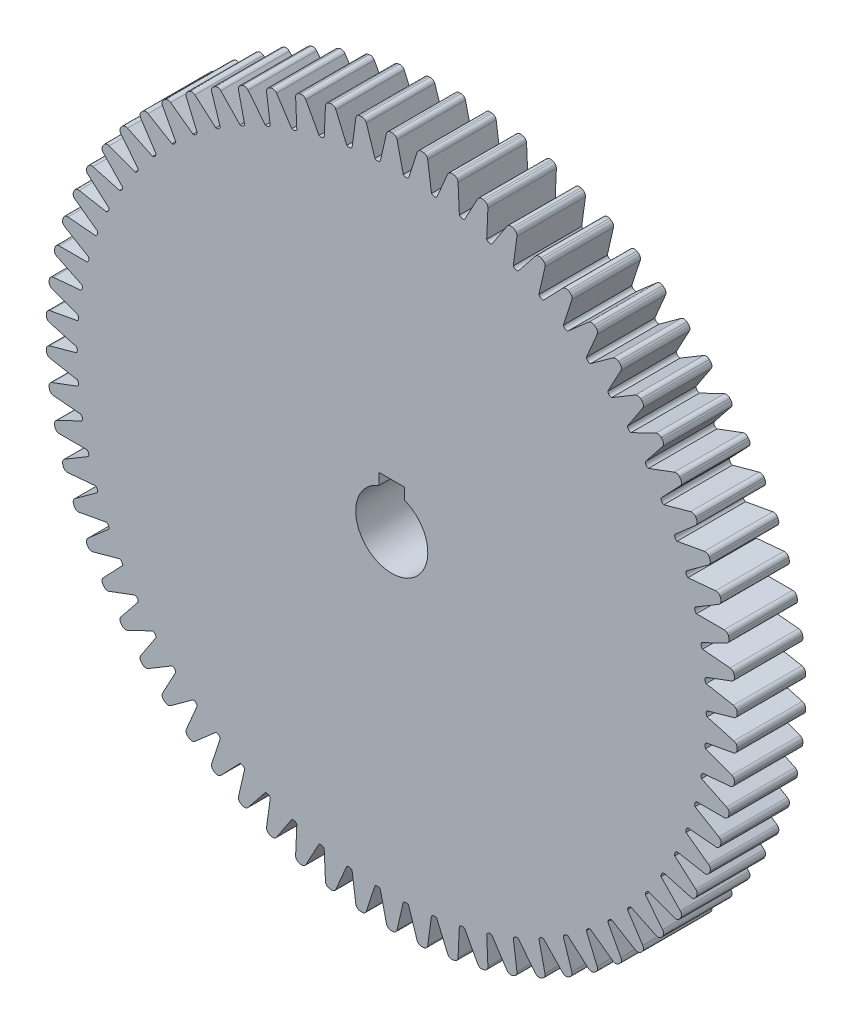
SolidWorks part; units mm, degrees
ref_plane "Front Plane" through (0, 0, 0) normal (0, 0, 1) x (1, 0, 0)
ref_plane "Top Plane" through (0, 0, 0) normal (0, 1, 0) x (1, 0, 0)
ref_plane "Right Plane" through (0, 0, 0) normal (1, 0, 0) x (0, 0, -1)
sketch "Sketch1" plane through (0, 0, 0) normal (0, 0, 1) x (1, 0, 0)
  line L0 (0, 0) -> (0, 6.9703) construction
  line L1 (-0.1016, 38.3651) -> (0.1016, 38.3651)
  line L2 (-0.5889, 37.9767) -> (-1.276, 34.9767)
  line L3 (0.5889, 37.9767) -> (1.276, 34.9767)
  line L4 (3.3379, 38.2198) -> (3.5402, 38.2016)
  line L5 (3.9908, 37.7711) -> (4.4061, 34.7216)
  line L6 (2.8176, 37.8766) -> (1.8645, 34.9503)
  line L7 (6.7504, 37.7667) -> (6.9503, 37.7304)
  line L8 (7.3605, 37.2613) -> (7.5008, 34.1868)
  line L9 (6.2015, 37.4716) -> (4.9899, 34.6425)
  line L10 (10.1086, 37.0096) -> (10.3044, 36.9555)
  line L11 (10.6709, 36.4515) -> (10.5351, 33.3768)
  line L12 (9.5355, 36.7648) -> (8.0751, 34.0557)
  line L13 (13.3855, 35.9544) -> (13.5756, 35.8831)
  line L14 (13.8955, 35.3482) -> (13.4845, 32.2981)
  line L15 (12.7927, 35.7621) -> (11.0953, 33.1948)
  line L16 (16.5545, 34.6098) -> (16.7375, 34.5217)
  line L17 (17.0081, 33.9603) -> (16.3254, 30.9593)
  line L18 (15.9469, 34.4714) -> (14.0262, 32.0666)
  line L19 (19.5903, 32.9866) -> (19.7646, 32.8824)
  line L20 (19.9838, 32.299) -> (19.0349, 29.3713)
  line L21 (18.9727, 32.9031) -> (16.8442, 30.6802)
  line L22 (22.4683, 31.0977) -> (22.6326, 30.9783)
  line L23 (22.7986, 30.3777) -> (21.5911, 27.5468)
  line L24 (21.8457, 31.07) -> (19.5265, 29.0468)
  line L25 (25.1654, 28.9585) -> (25.3184, 28.8249)
  line L26 (25.4299, 28.2117) -> (23.9734, 25.5005)
  line L27 (24.5428, 28.9867) -> (22.0517, 27.1795)
  line L28 (27.6599, 26.5861) -> (27.8003, 26.4393)
  line L29 (27.8564, 25.8186) -> (26.1628, 23.2489)
  line L30 (27.0424, 26.67) -> (24.3992, 25.0934)
  line L31 (29.9317, 23.9997) -> (30.0584, 23.8409)
  line L32 (30.0586, 23.2177) -> (28.1415, 20.81)
  line L33 (29.3242, 24.1386) -> (26.5504, 22.8052)
  line L34 (31.9626, 21.22) -> (32.0745, 21.0505)
  line L35 (32.0188, 20.4298) -> (29.8936, 18.2037)
  line L36 (31.3699, 21.4128) -> (28.4877, 20.3335)
  line L37 (33.736, 18.2695) -> (33.8323, 18.0906)
  line L38 (33.7212, 17.4774) -> (31.405, 15.4508)
  line L39 (33.1631, 18.5146) -> (30.1957, 17.698)
  line L40 (35.2379, 15.1718) -> (35.3177, 14.9851)
  line L41 (35.1521, 14.3843) -> (32.6636, 12.5734)
  line L42 (34.6892, 15.4674) -> (31.6606, 14.92)
  line L43 (36.456, 11.9521) -> (36.5188, 11.7589)
  line L44 (36.3, 11.1753) -> (33.6591, 9.5949)
  line L45 (35.936, 12.2956) -> (32.8706, 12.0219)
  line L46 (37.3806, 8.6361) -> (37.4258, 8.438)
  line L47 (37.1556, 7.8764) -> (34.3837, 6.5391)
  line L48 (36.8935, 9.0248) -> (33.8159, 9.027)
  line L49 (38.0043, 5.2505) -> (38.0315, 5.0492)
  line L50 (37.7121, 4.5141) -> (34.8315, 3.4306)
  line L51 (37.554, 5.6814) -> (34.4889, 5.9595)
  line L52 (38.3219, 1.8227) -> (38.331, 1.6198)
  line L53 (37.9649, 1.1155) -> (34.9988, 0.2945)
  line L54 (37.9121, 2.2922) -> (34.8843, 2.8439)
  line L55 (38.331, -1.6198) -> (38.3219, -1.8227)
  line L56 (37.9121, -2.2922) -> (34.8843, -2.8439)
  line L57 (37.9649, -1.1155) -> (34.9988, -0.2945)
  line L58 (38.0315, -5.0492) -> (38.0043, -5.2505)
  line L59 (37.554, -5.6814) -> (34.4889, -5.9595)
  line L60 (37.7121, -4.5141) -> (34.8315, -3.4306)
  line L61 (37.4258, -8.438) -> (37.3806, -8.6361)
  line L62 (36.8935, -9.0248) -> (33.8159, -9.027)
  line L63 (37.1556, -7.8764) -> (34.3837, -6.5391)
  line L64 (36.5188, -11.7589) -> (36.456, -11.9521)
  line L65 (35.936, -12.2956) -> (32.8706, -12.0219)
  line L66 (36.3, -11.1753) -> (33.6591, -9.5949)
  line L67 (35.3177, -14.9851) -> (35.2379, -15.1718)
  line L68 (34.6892, -15.4674) -> (31.6606, -14.92)
  line L69 (35.1521, -14.3843) -> (32.6636, -12.5734)
  line L70 (33.8323, -18.0906) -> (33.736, -18.2695)
  line L71 (33.1631, -18.5146) -> (30.1957, -17.698)
  line L72 (33.7212, -17.4774) -> (31.405, -15.4508)
  line L73 (32.0745, -21.0505) -> (31.9626, -21.22)
  line L74 (31.3699, -21.4128) -> (28.4877, -20.3335)
  line L75 (32.0188, -20.4298) -> (29.8936, -18.2037)
  line L76 (30.0584, -23.8409) -> (29.9317, -23.9997)
  line L77 (29.3242, -24.1386) -> (26.5504, -22.8052)
  line L78 (30.0586, -23.2177) -> (28.1415, -20.81)
  line L79 (27.8003, -26.4393) -> (27.6599, -26.5861)
  line L80 (27.0424, -26.67) -> (24.3992, -25.0934)
  line L81 (27.8564, -25.8186) -> (26.1628, -23.2489)
  line L82 (25.3184, -28.8249) -> (25.1654, -28.9585)
  line L83 (24.5428, -28.9867) -> (22.0517, -27.1795)
  line L84 (25.4299, -28.2117) -> (23.9734, -25.5005)
  line L85 (22.6326, -30.9783) -> (22.4683, -31.0977)
  line L86 (21.8457, -31.07) -> (19.5265, -29.0468)
  line L87 (22.7986, -30.3777) -> (21.5911, -27.5468)
  line L88 (19.7646, -32.8824) -> (19.5903, -32.9866)
  line L89 (18.9727, -32.9031) -> (16.8442, -30.6802)
  line L90 (19.9838, -32.299) -> (19.0349, -29.3713)
  line L91 (16.7375, -34.5217) -> (16.5545, -34.6098)
  line L92 (15.9469, -34.4714) -> (14.0262, -32.0666)
  line L93 (17.0081, -33.9603) -> (16.3254, -30.9593)
  line L94 (13.5756, -35.8831) -> (13.3855, -35.9544)
  line L95 (12.7927, -35.7621) -> (11.0953, -33.1948)
  line L96 (13.8955, -35.3482) -> (13.4845, -32.2981)
  line L97 (10.3044, -36.9555) -> (10.1086, -37.0096)
  line L98 (9.5355, -36.7648) -> (8.0751, -34.0557)
  line L99 (10.6709, -36.4515) -> (10.5351, -33.3768)
  line L100 (6.9503, -37.7304) -> (6.7504, -37.7667)
  line L101 (6.2015, -37.4716) -> (4.9899, -34.6425)
  line L102 (7.3605, -37.2613) -> (7.5008, -34.1868)
  line L103 (3.5402, -38.2016) -> (3.3379, -38.2198)
  line L104 (2.8176, -37.8766) -> (1.8645, -34.9503)
  line L105 (3.9908, -37.7711) -> (4.4061, -34.7216)
  line L106 (0.1016, -38.3651) -> (-0.1016, -38.3651)
  line L107 (-0.5889, -37.9767) -> (-1.276, -34.9767)
  line L108 (0.5889, -37.9767) -> (1.276, -34.9767)
  line L109 (-3.3379, -38.2198) -> (-3.5402, -38.2016)
  line L110 (-3.9908, -37.7711) -> (-4.4061, -34.7216)
  line L111 (-2.8176, -37.8766) -> (-1.8645, -34.9503)
  line L112 (-6.7504, -37.7667) -> (-6.9503, -37.7304)
  line L113 (-7.3605, -37.2613) -> (-7.5008, -34.1868)
  line L114 (-6.2015, -37.4716) -> (-4.9899, -34.6425)
  line L115 (-10.1086, -37.0096) -> (-10.3044, -36.9555)
  line L116 (-10.6709, -36.4515) -> (-10.5351, -33.3768)
  line L117 (-9.5355, -36.7648) -> (-8.0751, -34.0557)
  line L118 (-13.3855, -35.9544) -> (-13.5756, -35.8831)
  line L119 (-13.8955, -35.3482) -> (-13.4845, -32.2981)
  line L120 (-12.7927, -35.7621) -> (-11.0953, -33.1948)
  line L121 (-16.5545, -34.6098) -> (-16.7375, -34.5217)
  line L122 (-17.0081, -33.9603) -> (-16.3254, -30.9593)
  line L123 (-15.9469, -34.4714) -> (-14.0262, -32.0666)
  line L124 (-19.5903, -32.9866) -> (-19.7646, -32.8824)
  line L125 (-19.9838, -32.299) -> (-19.0349, -29.3713)
  line L126 (-18.9727, -32.9031) -> (-16.8442, -30.6802)
  line L127 (-22.4683, -31.0977) -> (-22.6326, -30.9783)
  line L128 (-22.7986, -30.3777) -> (-21.5911, -27.5468)
  line L129 (-21.8457, -31.07) -> (-19.5265, -29.0468)
  line L130 (-25.1654, -28.9585) -> (-25.3184, -28.8249)
  line L131 (-25.4299, -28.2117) -> (-23.9734, -25.5005)
  line L132 (-24.5428, -28.9867) -> (-22.0517, -27.1795)
  line L133 (-27.6599, -26.5861) -> (-27.8003, -26.4393)
  line L134 (-27.8564, -25.8186) -> (-26.1628, -23.2489)
  line L135 (-27.0424, -26.67) -> (-24.3992, -25.0934)
  line L136 (-29.9317, -23.9997) -> (-30.0584, -23.8409)
  line L137 (-30.0586, -23.2177) -> (-28.1415, -20.81)
  line L138 (-29.3242, -24.1386) -> (-26.5504, -22.8052)
  line L139 (-31.9626, -21.22) -> (-32.0745, -21.0505)
  line L140 (-32.0188, -20.4298) -> (-29.8936, -18.2037)
  line L141 (-31.3699, -21.4128) -> (-28.4877, -20.3335)
  line L142 (-33.736, -18.2695) -> (-33.8323, -18.0906)
  line L143 (-33.7212, -17.4774) -> (-31.405, -15.4508)
  line L144 (-33.1631, -18.5146) -> (-30.1957, -17.698)
  line L145 (-35.2379, -15.1718) -> (-35.3177, -14.9851)
  line L146 (-35.1521, -14.3843) -> (-32.6636, -12.5734)
  line L147 (-34.6892, -15.4674) -> (-31.6606, -14.92)
  line L148 (-36.456, -11.9521) -> (-36.5188, -11.7589)
  line L149 (-36.3, -11.1753) -> (-33.6591, -9.5949)
  line L150 (-35.936, -12.2956) -> (-32.8706, -12.0219)
  line L151 (-37.3806, -8.6361) -> (-37.4258, -8.438)
  line L152 (-37.1556, -7.8764) -> (-34.3837, -6.5391)
  line L153 (-36.8935, -9.0248) -> (-33.8159, -9.027)
  line L154 (-38.0043, -5.2505) -> (-38.0315, -5.0492)
  line L155 (-37.7121, -4.5141) -> (-34.8315, -3.4306)
  line L156 (-37.554, -5.6814) -> (-34.4889, -5.9595)
  line L157 (-38.3219, -1.8227) -> (-38.331, -1.6198)
  line L158 (-37.9649, -1.1155) -> (-34.9988, -0.2945)
  line L159 (-37.9121, -2.2922) -> (-34.8843, -2.8439)
  line L160 (-38.331, 1.6198) -> (-38.3219, 1.8227)
  line L161 (-37.9121, 2.2922) -> (-34.8843, 2.8439)
  line L162 (-37.9649, 1.1155) -> (-34.9988, 0.2945)
  line L163 (-38.0315, 5.0492) -> (-38.0043, 5.2505)
  line L164 (-37.554, 5.6814) -> (-34.4889, 5.9595)
  line L165 (-37.7121, 4.5141) -> (-34.8315, 3.4306)
  line L166 (-37.4258, 8.438) -> (-37.3806, 8.6361)
  line L167 (-36.8935, 9.0248) -> (-33.8159, 9.027)
  line L168 (-37.1556, 7.8764) -> (-34.3837, 6.5391)
  line L169 (-36.5188, 11.7589) -> (-36.456, 11.9521)
  line L170 (-35.936, 12.2956) -> (-32.8706, 12.0219)
  line L171 (-36.3, 11.1753) -> (-33.6591, 9.5949)
  line L172 (-35.3177, 14.9851) -> (-35.2379, 15.1718)
  line L173 (-34.6892, 15.4674) -> (-31.6606, 14.92)
  line L174 (-35.1521, 14.3843) -> (-32.6636, 12.5734)
  line L175 (-33.8323, 18.0906) -> (-33.736, 18.2695)
  line L176 (-33.1631, 18.5146) -> (-30.1957, 17.698)
  line L177 (-33.7212, 17.4774) -> (-31.405, 15.4508)
  line L178 (-32.0745, 21.0505) -> (-31.9626, 21.22)
  line L179 (-31.3699, 21.4128) -> (-28.4877, 20.3335)
  line L180 (-32.0188, 20.4298) -> (-29.8936, 18.2037)
  line L181 (-30.0584, 23.8409) -> (-29.9317, 23.9997)
  line L182 (-29.3242, 24.1386) -> (-26.5504, 22.8052)
  line L183 (-30.0586, 23.2177) -> (-28.1415, 20.81)
  line L184 (-27.8003, 26.4393) -> (-27.6599, 26.5861)
  line L185 (-27.0424, 26.67) -> (-24.3992, 25.0934)
  line L186 (-27.8564, 25.8186) -> (-26.1628, 23.2489)
  line L187 (-25.3184, 28.8249) -> (-25.1654, 28.9585)
  line L188 (-24.5428, 28.9867) -> (-22.0517, 27.1795)
  line L189 (-25.4299, 28.2117) -> (-23.9734, 25.5005)
  line L190 (-22.6326, 30.9783) -> (-22.4683, 31.0977)
  line L191 (-21.8457, 31.07) -> (-19.5265, 29.0468)
  line L192 (-22.7986, 30.3777) -> (-21.5911, 27.5468)
  line L193 (-19.7646, 32.8824) -> (-19.5903, 32.9866)
  line L194 (-18.9727, 32.9031) -> (-16.8442, 30.6802)
  line L195 (-19.9838, 32.299) -> (-19.0349, 29.3713)
  line L196 (-16.7375, 34.5217) -> (-16.5545, 34.6098)
  line L197 (-15.9469, 34.4714) -> (-14.0262, 32.0666)
  line L198 (-17.0081, 33.9603) -> (-16.3254, 30.9593)
  line L199 (-13.5756, 35.8831) -> (-13.3855, 35.9544)
  line L200 (-12.7927, 35.7621) -> (-11.0953, 33.1948)
  line L201 (-13.8955, 35.3482) -> (-13.4845, 32.2981)
  line L202 (-10.3044, 36.9555) -> (-10.1086, 37.0096)
  line L203 (-9.5355, 36.7648) -> (-8.0751, 34.0557)
  line L204 (-10.6709, 36.4515) -> (-10.5351, 33.3768)
  line L205 (-6.9503, 37.7304) -> (-6.7504, 37.7667)
  line L206 (-6.2015, 37.4716) -> (-4.9899, 34.6425)
  line L207 (-7.3605, 37.2613) -> (-7.5008, 34.1868)
  line L208 (-3.5402, 38.2016) -> (-3.3379, 38.2198)
  line L209 (-2.8176, 37.8766) -> (-1.8645, 34.9503)
  line L210 (-3.9908, 37.7711) -> (-4.4061, 34.7216)
  arc A1 (0.1016, 38.3651) -> (0.5889, 37.9767) centre (0.1016, 37.8651) cw
  arc A2 (-0.1016, 38.3651) -> (-0.5889, 37.9767) centre (-0.1016, 37.8651) ccw
  arc A281 (3.3379, 38.2198) -> (2.8176, 37.8766) centre (3.2931, 37.7218) ccw
  arc A282 (3.5402, 38.2016) -> (3.9908, 37.7711) centre (3.4954, 37.7036) cw
  arc A283 (6.7504, 37.7667) -> (6.2015, 37.4716) centre (6.6612, 37.2747) ccw
  arc A284 (6.9503, 37.7304) -> (7.3605, 37.2613) centre (6.861, 37.2385) cw
  arc A285 (10.1086, 37.0096) -> (9.5355, 36.7648) centre (9.9756, 36.5276) ccw
  arc A286 (10.3044, 36.9555) -> (10.6709, 36.4515) centre (10.1714, 36.4736) cw
  arc A287 (13.3855, 35.9544) -> (12.7927, 35.7621) centre (13.2098, 35.4863) ccw
  arc A288 (13.5756, 35.8831) -> (13.8955, 35.3482) centre (13.3999, 35.415) cw
  arc A289 (16.5545, 34.6098) -> (15.9469, 34.4714) centre (16.3376, 34.1594) ccw
  arc A290 (16.7375, 34.5217) -> (17.0081, 33.9603) centre (16.5206, 34.0712) cw
  arc A291 (19.5903, 32.9866) -> (18.9727, 32.9031) centre (19.3338, 32.5574) ccw
  arc A292 (19.7646, 32.8824) -> (19.9838, 32.299) centre (19.5082, 32.4532) cw
  arc A293 (22.4683, 31.0977) -> (21.8457, 31.07) centre (22.1744, 30.6932) ccw
  arc A294 (22.6326, 30.9783) -> (22.7986, 30.3777) centre (22.3387, 30.5738) cw
  arc A295 (25.1654, 28.9585) -> (24.5428, 28.9867) centre (24.8364, 28.582) ccw
  arc A296 (25.3184, 28.8249) -> (25.4299, 28.2117) centre (24.9894, 28.4483) cw
  arc A297 (27.6599, 26.5861) -> (27.0424, 26.67) centre (27.2985, 26.2406) ccw
  arc A298 (27.8003, 26.4393) -> (27.8564, 25.8186) centre (27.4389, 26.0938) cw
  arc A299 (29.9317, 23.9997) -> (29.3242, 24.1386) centre (29.5408, 23.6879) ccw
  arc A300 (30.0584, 23.8409) -> (30.0586, 23.2177) centre (29.6675, 23.5291) cw
  arc A301 (31.9626, 21.22) -> (31.3699, 21.4128) centre (31.5453, 20.9445) ccw
  arc A302 (32.0745, 21.0505) -> (32.0188, 20.4298) centre (31.6572, 20.775) cw
  arc A303 (33.736, 18.2695) -> (33.1631, 18.5146) centre (33.2957, 18.0325) ccw
  arc A304 (33.8323, 18.0906) -> (33.7212, 17.4774) centre (33.392, 17.8537) cw
  arc A305 (35.2379, 15.1718) -> (34.6892, 15.4674) centre (34.7781, 14.9753) ccw
  arc A306 (35.3177, 14.9851) -> (35.1521, 14.3843) centre (34.8579, 14.7886) cw
  arc A307 (36.456, 11.9521) -> (35.936, 12.2956) centre (35.9805, 11.7976) ccw
  arc A308 (36.5188, 11.7589) -> (36.3, 11.1753) centre (36.0433, 11.6044) cw
  arc A309 (37.3806, 8.6361) -> (36.8935, 9.0248) centre (36.8932, 8.5248) ccw
  arc A310 (37.4258, 8.438) -> (37.1556, 7.8764) centre (36.9384, 8.3268) cw
  arc A311 (38.0043, 5.2505) -> (37.554, 5.6814) centre (37.5088, 5.1834) ccw
  arc A312 (38.0315, 5.0492) -> (37.7121, 4.5141) centre (37.5361, 4.9821) cw
  arc A313 (38.3219, 1.8227) -> (37.9121, 2.2922) centre (37.8224, 1.8003) ccw
  arc A314 (38.331, 1.6198) -> (37.9649, 1.1155) centre (37.8315, 1.5974) cw
  arc A315 (38.331, -1.6198) -> (37.9649, -1.1155) centre (37.8315, -1.5974) ccw
  arc A316 (38.3219, -1.8227) -> (37.9121, -2.2922) centre (37.8224, -1.8003) cw
  arc A317 (38.0315, -5.0492) -> (37.7121, -4.5141) centre (37.5361, -4.9821) ccw
  arc A318 (38.0043, -5.2505) -> (37.554, -5.6814) centre (37.5088, -5.1834) cw
  arc A319 (37.4258, -8.438) -> (37.1556, -7.8764) centre (36.9384, -8.3268) ccw
  arc A320 (37.3806, -8.6361) -> (36.8935, -9.0248) centre (36.8932, -8.5248) cw
  arc A321 (36.5188, -11.7589) -> (36.3, -11.1753) centre (36.0433, -11.6044) ccw
  arc A322 (36.456, -11.9521) -> (35.936, -12.2956) centre (35.9805, -11.7976) cw
  arc A323 (35.3177, -14.9851) -> (35.1521, -14.3843) centre (34.8579, -14.7886) ccw
  arc A324 (35.2379, -15.1718) -> (34.6892, -15.4674) centre (34.7781, -14.9753) cw
  arc A325 (33.8323, -18.0906) -> (33.7212, -17.4774) centre (33.392, -17.8537) ccw
  arc A326 (33.736, -18.2695) -> (33.1631, -18.5146) centre (33.2957, -18.0325) cw
  arc A327 (32.0745, -21.0505) -> (32.0188, -20.4298) centre (31.6572, -20.775) ccw
  arc A328 (31.9626, -21.22) -> (31.3699, -21.4128) centre (31.5453, -20.9445) cw
  arc A329 (30.0584, -23.8409) -> (30.0586, -23.2177) centre (29.6675, -23.5291) ccw
  arc A330 (29.9317, -23.9997) -> (29.3242, -24.1386) centre (29.5408, -23.6879) cw
  arc A331 (27.8003, -26.4393) -> (27.8564, -25.8186) centre (27.4389, -26.0938) ccw
  arc A332 (27.6599, -26.5861) -> (27.0424, -26.67) centre (27.2985, -26.2406) cw
  arc A333 (25.3184, -28.8249) -> (25.4299, -28.2117) centre (24.9894, -28.4483) ccw
  arc A334 (25.1654, -28.9585) -> (24.5428, -28.9867) centre (24.8364, -28.582) cw
  arc A335 (22.6326, -30.9783) -> (22.7986, -30.3777) centre (22.3387, -30.5738) ccw
  arc A336 (22.4683, -31.0977) -> (21.8457, -31.07) centre (22.1744, -30.6932) cw
  arc A337 (19.7646, -32.8824) -> (19.9838, -32.299) centre (19.5082, -32.4532) ccw
  arc A338 (19.5903, -32.9866) -> (18.9727, -32.9031) centre (19.3338, -32.5574) cw
  arc A339 (16.7375, -34.5217) -> (17.0081, -33.9603) centre (16.5206, -34.0712) ccw
  arc A340 (16.5545, -34.6098) -> (15.9469, -34.4714) centre (16.3376, -34.1594) cw
  arc A341 (13.5756, -35.8831) -> (13.8955, -35.3482) centre (13.3999, -35.415) ccw
  arc A342 (13.3855, -35.9544) -> (12.7927, -35.7621) centre (13.2098, -35.4863) cw
  arc A343 (10.3044, -36.9555) -> (10.6709, -36.4515) centre (10.1714, -36.4736) ccw
  arc A344 (10.1086, -37.0096) -> (9.5355, -36.7648) centre (9.9756, -36.5276) cw
  arc A345 (6.9503, -37.7304) -> (7.3605, -37.2613) centre (6.861, -37.2385) ccw
  arc A346 (6.7504, -37.7667) -> (6.2015, -37.4716) centre (6.6612, -37.2747) cw
  arc A347 (3.5402, -38.2016) -> (3.9908, -37.7711) centre (3.4954, -37.7036) ccw
  arc A348 (3.3379, -38.2198) -> (2.8176, -37.8766) centre (3.2931, -37.7218) cw
  arc A349 (0.1016, -38.3651) -> (0.5889, -37.9767) centre (0.1016, -37.8651) ccw
  arc A350 (-0.1016, -38.3651) -> (-0.5889, -37.9767) centre (-0.1016, -37.8651) cw
  arc A351 (-3.3379, -38.2198) -> (-2.8176, -37.8766) centre (-3.2931, -37.7218) ccw
  arc A352 (-3.5402, -38.2016) -> (-3.9908, -37.7711) centre (-3.4954, -37.7036) cw
  arc A353 (-6.7504, -37.7667) -> (-6.2015, -37.4716) centre (-6.6612, -37.2747) ccw
  arc A354 (-6.9503, -37.7304) -> (-7.3605, -37.2613) centre (-6.861, -37.2385) cw
  arc A355 (-10.1086, -37.0096) -> (-9.5355, -36.7648) centre (-9.9756, -36.5276) ccw
  arc A356 (-10.3044, -36.9555) -> (-10.6709, -36.4515) centre (-10.1714, -36.4736) cw
  arc A357 (-13.3855, -35.9544) -> (-12.7927, -35.7621) centre (-13.2098, -35.4863) ccw
  arc A358 (-13.5756, -35.8831) -> (-13.8955, -35.3482) centre (-13.3999, -35.415) cw
  arc A359 (-16.5545, -34.6098) -> (-15.9469, -34.4714) centre (-16.3376, -34.1594) ccw
  arc A360 (-16.7375, -34.5217) -> (-17.0081, -33.9603) centre (-16.5206, -34.0712) cw
  arc A361 (-19.5903, -32.9866) -> (-18.9727, -32.9031) centre (-19.3338, -32.5574) ccw
  arc A362 (-19.7646, -32.8824) -> (-19.9838, -32.299) centre (-19.5082, -32.4532) cw
  arc A363 (-22.4683, -31.0977) -> (-21.8457, -31.07) centre (-22.1744, -30.6932) ccw
  arc A364 (-22.6326, -30.9783) -> (-22.7986, -30.3777) centre (-22.3387, -30.5738) cw
  arc A365 (-25.1654, -28.9585) -> (-24.5428, -28.9867) centre (-24.8364, -28.582) ccw
  arc A366 (-25.3184, -28.8249) -> (-25.4299, -28.2117) centre (-24.9894, -28.4483) cw
  arc A367 (-27.6599, -26.5861) -> (-27.0424, -26.67) centre (-27.2985, -26.2406) ccw
  arc A368 (-27.8003, -26.4393) -> (-27.8564, -25.8186) centre (-27.4389, -26.0938) cw
  arc A369 (-29.9317, -23.9997) -> (-29.3242, -24.1386) centre (-29.5408, -23.6879) ccw
  arc A370 (-30.0584, -23.8409) -> (-30.0586, -23.2177) centre (-29.6675, -23.5291) cw
  arc A371 (-31.9626, -21.22) -> (-31.3699, -21.4128) centre (-31.5453, -20.9445) ccw
  arc A372 (-32.0745, -21.0505) -> (-32.0188, -20.4298) centre (-31.6572, -20.775) cw
  arc A373 (-33.736, -18.2695) -> (-33.1631, -18.5146) centre (-33.2957, -18.0325) ccw
  arc A374 (-33.8323, -18.0906) -> (-33.7212, -17.4774) centre (-33.392, -17.8537) cw
  arc A375 (-35.2379, -15.1718) -> (-34.6892, -15.4674) centre (-34.7781, -14.9753) ccw
  arc A376 (-35.3177, -14.9851) -> (-35.1521, -14.3843) centre (-34.8579, -14.7886) cw
  arc A377 (-36.456, -11.9521) -> (-35.936, -12.2956) centre (-35.9805, -11.7976) ccw
  arc A378 (-36.5188, -11.7589) -> (-36.3, -11.1753) centre (-36.0433, -11.6044) cw
  arc A379 (-37.3806, -8.6361) -> (-36.8935, -9.0248) centre (-36.8932, -8.5248) ccw
  arc A380 (-37.4258, -8.438) -> (-37.1556, -7.8764) centre (-36.9384, -8.3268) cw
  arc A381 (-38.0043, -5.2505) -> (-37.554, -5.6814) centre (-37.5088, -5.1834) ccw
  arc A382 (-38.0315, -5.0492) -> (-37.7121, -4.5141) centre (-37.5361, -4.9821) cw
  arc A383 (-38.3219, -1.8227) -> (-37.9121, -2.2922) centre (-37.8224, -1.8003) ccw
  arc A384 (-38.331, -1.6198) -> (-37.9649, -1.1155) centre (-37.8315, -1.5974) cw
  arc A385 (-38.331, 1.6198) -> (-37.9649, 1.1155) centre (-37.8315, 1.5974) ccw
  arc A386 (-38.3219, 1.8227) -> (-37.9121, 2.2922) centre (-37.8224, 1.8003) cw
  arc A387 (-38.0315, 5.0492) -> (-37.7121, 4.5141) centre (-37.5361, 4.9821) ccw
  arc A388 (-38.0043, 5.2505) -> (-37.554, 5.6814) centre (-37.5088, 5.1834) cw
  arc A389 (-37.4258, 8.438) -> (-37.1556, 7.8764) centre (-36.9384, 8.3268) ccw
  arc A390 (-37.3806, 8.6361) -> (-36.8935, 9.0248) centre (-36.8932, 8.5248) cw
  arc A391 (-36.5188, 11.7589) -> (-36.3, 11.1753) centre (-36.0433, 11.6044) ccw
  arc A392 (-36.456, 11.9521) -> (-35.936, 12.2956) centre (-35.9805, 11.7976) cw
  arc A393 (-35.3177, 14.9851) -> (-35.1521, 14.3843) centre (-34.8579, 14.7886) ccw
  arc A394 (-35.2379, 15.1718) -> (-34.6892, 15.4674) centre (-34.7781, 14.9753) cw
  arc A395 (-33.8323, 18.0906) -> (-33.7212, 17.4774) centre (-33.392, 17.8537) ccw
  arc A396 (-33.736, 18.2695) -> (-33.1631, 18.5146) centre (-33.2957, 18.0325) cw
  arc A397 (-32.0745, 21.0505) -> (-32.0188, 20.4298) centre (-31.6572, 20.775) ccw
  arc A398 (-31.9626, 21.22) -> (-31.3699, 21.4128) centre (-31.5453, 20.9445) cw
  arc A399 (-30.0584, 23.8409) -> (-30.0586, 23.2177) centre (-29.6675, 23.5291) ccw
  arc A400 (-29.9317, 23.9997) -> (-29.3242, 24.1386) centre (-29.5408, 23.6879) cw
  arc A401 (-27.8003, 26.4393) -> (-27.8564, 25.8186) centre (-27.4389, 26.0938) ccw
  arc A402 (-27.6599, 26.5861) -> (-27.0424, 26.67) centre (-27.2985, 26.2406) cw
  arc A403 (-25.3184, 28.8249) -> (-25.4299, 28.2117) centre (-24.9894, 28.4483) ccw
  arc A404 (-25.1654, 28.9585) -> (-24.5428, 28.9867) centre (-24.8364, 28.582) cw
  arc A405 (-22.6326, 30.9783) -> (-22.7986, 30.3777) centre (-22.3387, 30.5738) ccw
  arc A406 (-22.4683, 31.0977) -> (-21.8457, 31.07) centre (-22.1744, 30.6932) cw
  arc A407 (-19.7646, 32.8824) -> (-19.9838, 32.299) centre (-19.5082, 32.4532) ccw
  arc A408 (-19.5903, 32.9866) -> (-18.9727, 32.9031) centre (-19.3338, 32.5574) cw
  arc A409 (-16.7375, 34.5217) -> (-17.0081, 33.9603) centre (-16.5206, 34.0712) ccw
  arc A410 (-16.5545, 34.6098) -> (-15.9469, 34.4714) centre (-16.3376, 34.1594) cw
  arc A411 (-13.5756, 35.8831) -> (-13.8955, 35.3482) centre (-13.3999, 35.415) ccw
  arc A412 (-13.3855, 35.9544) -> (-12.7927, 35.7621) centre (-13.2098, 35.4863) cw
  arc A413 (-10.3044, 36.9555) -> (-10.6709, 36.4515) centre (-10.1714, 36.4736) ccw
  arc A414 (-10.1086, 37.0096) -> (-9.5355, 36.7648) centre (-9.9756, 36.5276) cw
  arc A415 (-6.9503, 37.7304) -> (-7.3605, 37.2613) centre (-6.861, 37.2385) ccw
  arc A416 (-6.7504, 37.7667) -> (-6.2015, 37.4716) centre (-6.6612, 37.2747) cw
  arc A417 (-3.5402, 38.2016) -> (-3.9908, 37.7711) centre (-3.4954, 37.7036) ccw
  arc A418 (-3.3379, 38.2198) -> (-2.8176, 37.8766) centre (-3.2931, 37.7218) cw
  spline S0 degree 2 poles (1.276, 34.9767) (1.5601, 34.7601) (1.8645, 34.9503) knots 0 0 0 1 1 1
  spline S1 degree 2 poles (4.4061, 34.7216) (4.6697, 34.4803) (4.9899, 34.6425) knots 0 0 0 1 1 1
  spline S2 degree 2 poles (7.5008, 34.1868) (7.7417, 33.9229) (8.0751, 34.0557) knots 0 0 0 1 1 1
  spline S3 degree 2 poles (10.5351, 33.3768) (10.7514, 33.0924) (11.0953, 33.1948) knots 0 0 0 1 1 1
  spline S4 degree 2 poles (13.4845, 32.2981) (13.6745, 31.9955) (14.0262, 32.0666) knots 0 0 0 1 1 1
  spline S5 degree 2 poles (16.3254, 30.9593) (16.4875, 30.6409) (16.8442, 30.6802) knots 0 0 0 1 1 1
  spline S6 degree 2 poles (19.0349, 29.3713) (19.1677, 29.0396) (19.5265, 29.0468) knots 0 0 0 1 1 1
  spline S7 degree 2 poles (21.5911, 27.5468) (21.6937, 27.2045) (22.0517, 27.1795) knots 0 0 0 1 1 1
  spline S8 degree 2 poles (23.9734, 25.5005) (24.0449, 25.1504) (24.3992, 25.0934) knots 0 0 0 1 1 1
  spline S9 degree 2 poles (26.1628, 23.2489) (26.2026, 22.8938) (26.5504, 22.8052) knots 0 0 0 1 1 1
  spline S10 degree 2 poles (28.1415, 20.81) (28.1493, 20.4528) (28.4877, 20.3335) knots 0 0 0 1 1 1
  spline S11 degree 2 poles (29.8936, 18.2037) (29.8693, 17.8472) (30.1957, 17.698) knots 0 0 0 1 1 1
  spline S12 degree 2 poles (31.405, 15.4508) (31.3489, 15.0979) (31.6606, 14.92) knots 0 0 0 1 1 1
  spline S13 degree 2 poles (32.6636, 12.5734) (32.5761, 12.227) (32.8706, 12.0219) knots 0 0 0 1 1 1
  spline S14 degree 2 poles (33.6591, 9.5949) (33.5409, 9.2577) (33.8159, 9.027) knots 0 0 0 1 1 1
  spline S15 degree 2 poles (34.3837, 6.5391) (34.2358, 6.2138) (34.4889, 5.9595) knots 0 0 0 1 1 1
  spline S16 degree 2 poles (34.8315, 3.4306) (34.655, 3.12) (34.8843, 2.8439) knots 0 0 0 1 1 1
  spline S17 degree 2 poles (34.9988, 0.2945) (34.7951, 0.001) (34.9988, -0.2945) knots 0 0 0 1 1 1
  spline S18 degree 2 poles (34.8843, -2.8439) (34.6551, -3.1181) (34.8315, -3.4306) knots 0 0 0 1 1 1
  spline S19 degree 2 poles (34.4889, -5.9595) (34.2361, -6.212) (34.3837, -6.5391) knots 0 0 0 1 1 1
  spline S20 degree 2 poles (33.8159, -9.027) (33.5415, -9.2559) (33.6591, -9.5949) knots 0 0 0 1 1 1
  spline S21 degree 2 poles (32.8706, -12.0219) (32.5767, -12.2252) (32.6636, -12.5734) knots 0 0 0 1 1 1
  spline S22 degree 2 poles (31.6606, -14.92) (31.3497, -15.0962) (31.405, -15.4508) knots 0 0 0 1 1 1
  spline S23 degree 2 poles (30.1957, -17.698) (29.8703, -17.8456) (29.8936, -18.2037) knots 0 0 0 1 1 1
  spline S24 degree 2 poles (28.4877, -20.3335) (28.1504, -20.4513) (28.1415, -20.81) knots 0 0 0 1 1 1
  spline S25 degree 2 poles (26.5504, -22.8052) (26.2038, -22.8923) (26.1628, -23.2489) knots 0 0 0 1 1 1
  spline S26 degree 2 poles (24.3992, -25.0934) (24.0463, -25.1491) (23.9734, -25.5005) knots 0 0 0 1 1 1
  spline S27 degree 2 poles (22.0517, -27.1795) (21.6951, -27.2033) (21.5911, -27.5468) knots 0 0 0 1 1 1
  spline S28 degree 2 poles (19.5265, -29.0468) (19.1693, -29.0386) (19.0349, -29.3713) knots 0 0 0 1 1 1
  spline S29 degree 2 poles (16.8442, -30.6802) (16.4892, -30.64) (16.3254, -30.9593) knots 0 0 0 1 1 1
  spline S30 degree 2 poles (14.0262, -32.0666) (13.6762, -31.9947) (13.4845, -32.2981) knots 0 0 0 1 1 1
  spline S31 degree 2 poles (11.0953, -33.1948) (10.7532, -33.0918) (10.5351, -33.3768) knots 0 0 0 1 1 1
  spline S32 degree 2 poles (8.0751, -34.0557) (7.7436, -33.9225) (7.5008, -34.1868) knots 0 0 0 1 1 1
  spline S33 degree 2 poles (4.9899, -34.6425) (4.6716, -34.4801) (4.4061, -34.7216) knots 0 0 0 1 1 1
  spline S34 degree 2 poles (1.8645, -34.9503) (1.562, -34.76) (1.276, -34.9767) knots 0 0 0 1 1 1
  spline S35 degree 2 poles (-1.276, -34.9767) (-1.5601, -34.7601) (-1.8645, -34.9503) knots 0 0 0 1 1 1
  spline S36 degree 2 poles (-4.4061, -34.7216) (-4.6697, -34.4803) (-4.9899, -34.6425) knots 0 0 0 1 1 1
  spline S37 degree 2 poles (-7.5008, -34.1868) (-7.7417, -33.9229) (-8.0751, -34.0557) knots 0 0 0 1 1 1
  spline S38 degree 2 poles (-10.5351, -33.3768) (-10.7514, -33.0924) (-11.0953, -33.1948) knots 0 0 0 1 1 1
  spline S39 degree 2 poles (-13.4845, -32.2981) (-13.6745, -31.9955) (-14.0262, -32.0666) knots 0 0 0 1 1 1
  spline S40 degree 2 poles (-16.3254, -30.9593) (-16.4875, -30.6409) (-16.8442, -30.6802) knots 0 0 0 1 1 1
  spline S41 degree 2 poles (-19.0349, -29.3713) (-19.1677, -29.0396) (-19.5265, -29.0468) knots 0 0 0 1 1 1
  spline S42 degree 2 poles (-21.5911, -27.5468) (-21.6937, -27.2045) (-22.0517, -27.1795) knots 0 0 0 1 1 1
  spline S43 degree 2 poles (-23.9734, -25.5005) (-24.0449, -25.1504) (-24.3992, -25.0934) knots 0 0 0 1 1 1
  spline S44 degree 2 poles (-26.1628, -23.2489) (-26.2026, -22.8938) (-26.5504, -22.8052) knots 0 0 0 1 1 1
  spline S45 degree 2 poles (-28.1415, -20.81) (-28.1493, -20.4528) (-28.4877, -20.3335) knots 0 0 0 1 1 1
  spline S46 degree 2 poles (-29.8936, -18.2037) (-29.8693, -17.8472) (-30.1957, -17.698) knots 0 0 0 1 1 1
  spline S47 degree 2 poles (-31.405, -15.4508) (-31.3489, -15.0979) (-31.6606, -14.92) knots 0 0 0 1 1 1
  spline S48 degree 2 poles (-32.6636, -12.5734) (-32.5761, -12.227) (-32.8706, -12.0219) knots 0 0 0 1 1 1
  spline S49 degree 2 poles (-33.6591, -9.5949) (-33.5409, -9.2577) (-33.8159, -9.027) knots 0 0 0 1 1 1
  spline S50 degree 2 poles (-34.3837, -6.5391) (-34.2358, -6.2138) (-34.4889, -5.9595) knots 0 0 0 1 1 1
  spline S51 degree 2 poles (-34.8315, -3.4306) (-34.655, -3.12) (-34.8843, -2.8439) knots 0 0 0 1 1 1
  spline S52 degree 2 poles (-34.9988, -0.2945) (-34.7951, -0.001) (-34.9988, 0.2945) knots 0 0 0 1 1 1
  spline S53 degree 2 poles (-34.8843, 2.8439) (-34.6551, 3.1181) (-34.8315, 3.4306) knots 0 0 0 1 1 1
  spline S54 degree 2 poles (-34.4889, 5.9595) (-34.2361, 6.212) (-34.3837, 6.5391) knots 0 0 0 1 1 1
  spline S55 degree 2 poles (-33.8159, 9.027) (-33.5415, 9.2559) (-33.6591, 9.5949) knots 0 0 0 1 1 1
  spline S56 degree 2 poles (-32.8706, 12.0219) (-32.5767, 12.2252) (-32.6636, 12.5734) knots 0 0 0 1 1 1
  spline S57 degree 2 poles (-31.6606, 14.92) (-31.3497, 15.0962) (-31.405, 15.4508) knots 0 0 0 1 1 1
  spline S58 degree 2 poles (-30.1957, 17.698) (-29.8703, 17.8456) (-29.8936, 18.2037) knots 0 0 0 1 1 1
  spline S59 degree 2 poles (-28.4877, 20.3335) (-28.1504, 20.4513) (-28.1415, 20.81) knots 0 0 0 1 1 1
  spline S60 degree 2 poles (-26.5504, 22.8052) (-26.2038, 22.8923) (-26.1628, 23.2489) knots 0 0 0 1 1 1
  spline S61 degree 2 poles (-24.3992, 25.0934) (-24.0463, 25.1491) (-23.9734, 25.5005) knots 0 0 0 1 1 1
  spline S62 degree 2 poles (-22.0517, 27.1795) (-21.6951, 27.2033) (-21.5911, 27.5468) knots 0 0 0 1 1 1
  spline S63 degree 2 poles (-19.5265, 29.0468) (-19.1693, 29.0386) (-19.0349, 29.3713) knots 0 0 0 1 1 1
  spline S64 degree 2 poles (-16.8442, 30.6802) (-16.4892, 30.64) (-16.3254, 30.9593) knots 0 0 0 1 1 1
  spline S65 degree 2 poles (-14.0262, 32.0666) (-13.6762, 31.9947) (-13.4845, 32.2981) knots 0 0 0 1 1 1
  spline S66 degree 2 poles (-11.0953, 33.1948) (-10.7532, 33.0918) (-10.5351, 33.3768) knots 0 0 0 1 1 1
  spline S67 degree 2 poles (-8.0751, 34.0557) (-7.7436, 33.9225) (-7.5008, 34.1868) knots 0 0 0 1 1 1
  spline S68 degree 2 poles (-4.9899, 34.6425) (-4.6716, 34.4801) (-4.4061, 34.7216) knots 0 0 0 1 1 1
  spline S69 degree 2 poles (-1.8645, 34.9503) (-1.562, 34.76) (-1.276, 34.9767) knots 0 0 0 1 1 1
  point P7 (0, 38.3651)
  point P12 (0.5, 38.3651)
  point P15 (-0.5, 38.3651)
  point P569 (0, 0)
  point P891 (0, 0)
  dimension "D1" = 2.5519
  dimension "D4" = 0.5
  dimension "D5" = 70
  dimension "D2" = 3
  dimension "D3" = 0.2031
extrude "Boss-Extrude1" add sketch "Sketch1" along normal blind 7.6
sketch "Sketch5" plane through (0, 0, 0) normal (0, 0, -1) x (-1, 0, 0)
  line L2 (-1.4316, 3.735) -> (-1.4316, 5)
  line L3 (-1.4316, 5) -> (1.4316, 5)
  line L4 (1.4316, 3.735) -> (1.4316, 5)
  line L5 (0, 4) -> (1.4316, 5) construction
  line L6 (-1.4316, 5) -> (0, 4) construction
  arc A0 (-1.4316, 3.735) -> (1.4316, 3.735) centre (0, 0) ccw
  point P3 (0, 4)
  dimension "D1" = 8
  dimension "D2" = 5
extrude "Cut-Extrude2" cut sketch "Sketch5" against normal through all
